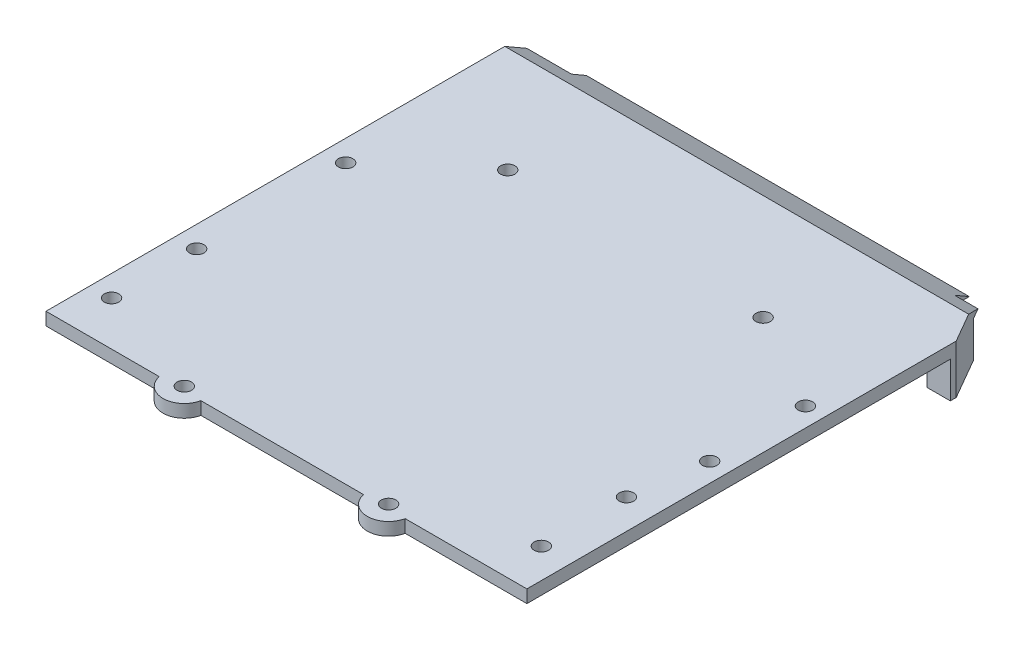
SolidWorks part; units mm, degrees
ref_plane "前视基准面" through (0, 0, 0) normal (0, 0, 1) x (1, 0, 0)
ref_plane "上视基准面" through (0, 0, 0) normal (0, 1, 0) x (1, 0, 0)
ref_plane "右视基准面" through (0, 0, 0) normal (1, 0, 0) x (0, 0, -1)
other "Configuration Table"
sketch "草图1" plane through (0, 0, 0) normal (0, 1, 0) x (1, 0, 0)
  line L1 (0, 0) -> (113, 0)
  line L2 (0, 0) -> (0, 113)
  line L3 (0, 113) -> (113, 113)
  line L4 (113, 0) -> (113, 113)
  dimension "D1" = 113
extrude "凸台-拉伸1" add sketch "草图1" along normal blind 3
sketch "草图2" plane through (0, 3, 0) normal (0, 1, 0) x (1, 0, 0)
  line L0 (108.5, 113) -> (108.5, 0) construction
  line L1 (113, 113) -> (0, 113) construction
  line L2 (0, 0) -> (113, 0) construction
  line L3 (113, 0) -> (113, 113) construction
  line L4 (106, 30.4) -> (106, 0) construction
  circle A0 centre (108.5, 69.95) radius 1.7
  circle A1 centre (108.5, 47.45) radius 1.7
  circle A2 centre (106, 30.4) radius 1.7
  circle A3 centre (106, 10.4) radius 1.7
  dimension "D2" = 47.45
  dimension "D3" = 22.5
  dimension "D4" = 3.4
  dimension "D6" = 10.4
  dimension "D7" = 20
  dimension "D1" = 4.5
  dimension "D5" = 7
extrude "切除-拉伸1" cut sketch "草图2" against normal up to next
sketch "草图3" plane through (0, 0, 0) normal (0, 1, 0) x (1, 0, 0)
  line L0 (113, 113) -> (0, 113) construction
  line L1 (10.5, 113) -> (100.5, 113)
  line L2 (10.5, 113) -> (10.5, 8)
  line L3 (10.5, 8) -> (100.5, 8)
  line L4 (100.5, 113) -> (100.5, 8)
  line L5 (113, 0) -> (113, 113) construction
  line L6 (0, 113) -> (0, 0) construction
  line L7 (0, 0) -> (113, 0) construction
  dimension "D1" = 12.5
  dimension "D2" = 10.5
  dimension "D3" = 8
extrude "凸台-拉伸2" add sketch "草图3" against normal blind 2
sketch "草图5" plane through (0, 0, 0) normal (0, -1, 0) x (1, 0, 0)
  line L0 (0, -1) -> (113, -1) construction
  line L1 (0, -113) -> (0, 0) construction
  line L2 (113, 0) -> (113, -113) construction
  line L3 (0, 0) -> (113, 0) construction
  circle A0 centre (79.5, -1) radius 5
  circle A1 centre (31.5, -1) radius 5
  dimension "D1" = 33.5
  dimension "D2" = 48
  dimension "D3" = 10
  dimension "D4" = 1
extrude "凸台-拉伸3" add sketch "草图5" against normal up to surface (3 mm away) up to face at (108.5, 3, -68.25)
sketch "草图6" plane through (0, 0, 0) normal (0, -1, 0) x (1, 0, 0)
  circle A0 centre (31.5, -1) radius 1.7
  circle A1 centre (79.5, -1) radius 1.7
  dimension "D1" = 3.4
extrude "切除-拉伸2" cut sketch "草图6" against normal up to next
sketch "草图7" plane through (0, 0, 0) normal (0, -1, 0) x (1, 0, 0)
  line L0 (5, 0) -> (5, -113) construction
  line L1 (0, 0) -> (26.601, 0) construction
  line L2 (10.5, -113) -> (0, -113) construction
  line L3 (0, -113) -> (0, 0) construction
  circle A0 centre (5, -10.4) radius 1.7
  circle A1 centre (5, -30.4) radius 1.7
  circle A2 centre (5, -65.4) radius 1.7
  dimension "D1" = 10.4
  dimension "D3" = 20
  dimension "D4" = 35
  dimension "D5" = 3.4
  dimension "D2" = 5
extrude "切除-拉伸3" cut sketch "草图7" against normal up to next
sketch "草图8" plane through (0, -2, 0) normal (0, -1, 0) x (1, 0, 0)
  line L0 (55.5, -8) -> (55.5, -113) construction
  line L1 (10.5, -8) -> (100.5, -8) construction
  line L2 (100.5, -113) -> (10.5, -113) construction
  circle A0 centre (25.5, -83) radius 1.7
  circle A1 centre (85.5, -83) radius 1.7
  dimension "D1" = 60
  dimension "D2" = 3.4
  dimension "D3" = 30
extrude "切除-拉伸4" cut sketch "草图8" against normal up to next
sketch "草图10" plane through (100.5, 0, 0) normal (1, 0, 0) x (0, 0, -1)
  line L0 (113, 0) -> (116.4641, -2)
  line L1 (116.4641, -2) -> (113, -2)
  line L2 (113, -2) -> (113, 0)
  dimension "D1" = 30
extrude "凸台-拉伸5" add sketch "草图10" against normal up to surface (90 mm away) up to face at (10.5, -1, -60.5)
sketch "草图11" plane through (0, -2, 0) normal (0, 1, 0) x (1, 0, 0)
  line L0 (20.5, 83) -> (20.5, 23)
  line L2 (30.5, 23) -> (30.5, 83)
  line L3 (80.5, 83) -> (80.5, 23)
  line L5 (90.5, 23) -> (90.5, 83)
  arc A0 (30.5, 83) -> (20.5, 83) centre (25.5, 83) ccw
  arc A1 (90.5, 83) -> (80.5, 83) centre (85.5, 83) ccw
  arc A2 (20.5, 23) -> (30.5, 23) centre (25.5, 23) ccw
  arc A3 (80.5, 23) -> (90.5, 23) centre (85.5, 23) ccw
  dimension "D1" = 10
  dimension "D2" = 60
extrude "切除-拉伸5" cut sketch "草图11" along normal blind 2
sketch "草图13" plane through (0, 0, 0) normal (0, -1, 0) x (1, 0, 0)
  line L0 (0, -113) -> (0, 0) construction
  line L1 (5, -89) -> (3, -89)
  line L2 (5, -89) -> (5, -77)
  line L3 (5, -77) -> (3, -77)
  line L4 (3, -89) -> (3, -77)
  line L7 (10.5, -113) -> (0, -113) construction
  dimension "D1" = 2
  dimension "D2" = 3
  dimension "D3" = 36
  dimension "D4" = 12
extrude "凸台-拉伸6" add sketch "草图13" along normal blind 11.5
sketch "草图14" plane through (3, 0, 0) normal (-1, 0, 0) x (0, 0, 1)
  line L1 (-113, 0) -> (0, 0) construction
  line L2 (-113, 3) -> (-113, 0) construction
  circle A0 centre (-83.5, -5) radius 1.7
  dimension "D1" = 3.4
  dimension "D2" = 29.5
  dimension "D3" = 5
extrude "切除-拉伸6" cut sketch "草图14" against normal up to next
sketch "草图15" plane through (0, 0, 0) normal (0, -1, 0) x (1, 0, 0)
  line L0 (113, -100.8756) -> (106, -113)
  line L1 (113, 0) -> (113, -113) construction
  line L2 (113, -113) -> (100.5, -113) construction
  line L3 (106, -113) -> (113, -113)
  line L4 (113, -113) -> (113, -100.8756)
  dimension "D1" = 7
  dimension "D2" = 60
extrude "切除-拉伸7" cut sketch "草图15" against normal up to next
sketch "草图16" plane through (0, 0, 0) normal (0, -1, 0) x (1, 0, 0)
  line L0 (113, -100.8756) -> (106, -113) construction
  line L1 (113, -99.5) -> (107.5, -99.5)
  line L4 (107.5, -99.5) -> (107.5, -110.4019)
  line L5 (106, -113) -> (100.5, -113) construction
  line L6 (113, 0) -> (113, -100.8756) construction
  line L7 (113, -100.8756) -> (107.5, -110.4019)
  line L8 (113, -99.5) -> (113, -100.8756)
  dimension "D1" = 13.5
  dimension "D2" = 5.5
extrude "凸台-拉伸7" add sketch "草图16" along normal blind 8.5
sketch "草图17" plane through (3, 0, 0) normal (-1, 0, 0) x (0, 0, 1)
  line L0 (-113, 0) -> (0, 0) construction
  line L1 (-77, -11.5) -> (-79, -11.5)
  line L2 (-77, -11.5) -> (-77, 0)
  line L3 (-77, 0) -> (-79, 0)
  line L4 (-79, -11.5) -> (-79, 0)
  dimension "D1" = 2
extrude "凸台-拉伸8" add sketch "草图17" along normal up to surface (3 mm away) up to face at (0, 1.5, -56.5)
fillet "圆角1" radius 1 1 edges at (3, -5.75, -79)
sketch "草图19" plane through (0, 0, 0) normal (-1, 0, 0) x (0, 0, 1)
  line L0 (-113, 0) -> (-107.8038, 3)
  line L1 (-113, 3) -> (0, 3) construction
  line L2 (-107.8038, 3) -> (-113, 3)
  line L3 (-113, 3) -> (-113, 0)
  dimension "D1" = 60
extrude "切除-拉伸8" cut sketch "草图19" against normal through all
